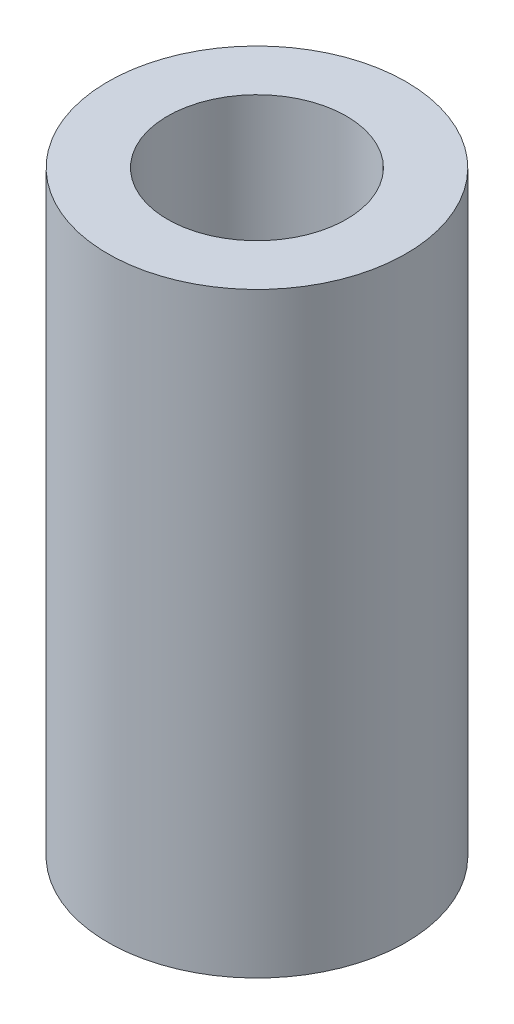
SolidWorks part; units mm, degrees
ref_plane "Alzado" through (0, 0, 0) normal (0, 0, 1) x (1, 0, 0)
ref_plane "Planta" through (0, 0, 0) normal (0, 1, 0) x (1, 0, 0)
ref_plane "Vista lateral" through (0, 0, 0) normal (1, 0, 0) x (0, 0, -1)
sketch "Croquis1" plane through (0, 0, 0) normal (0, 0, 1) x (1, 0, 0)
  line L0 (0, 0) -> (-1.5, 0) construction
  line L1 (-1.5, 0) -> (-2.5, 0)
  line L2 (-1.5, 0) -> (-1.5, 10)
  line L3 (-1.5, 10) -> (-2.5, 10)
  line L4 (-2.5, 10) -> (-2.5, 0)
  line L5 (0, 0) -> (0, 6) construction
  dimension "D1" = 1
  dimension "D2" = 1.5
  dimension "D3" = 10
revolve "Revolución1" add sketch "Croquis1" angle 360 about L5
